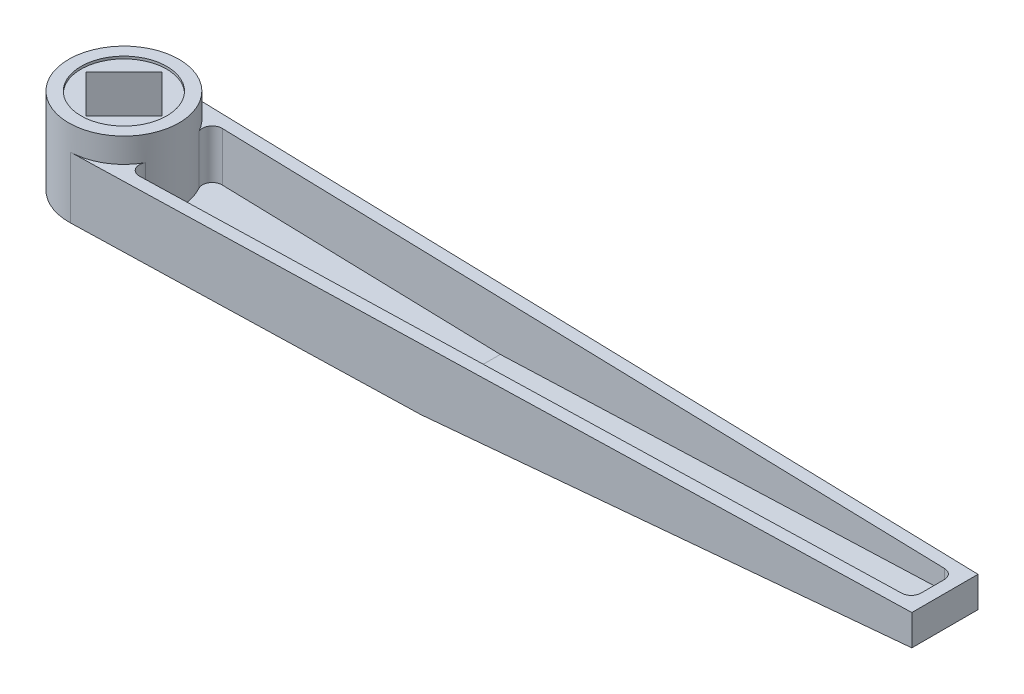
SolidWorks part; units mm, degrees
material "1060 Alloy"
ref_plane "XY" through (0, 0, 0) normal (0, 0, 1) x (1, 0, 0)
ref_plane "XZ" through (0, 0, 0) normal (0, 1, 0) x (1, 0, 0)
ref_plane "YZ" through (0, 0, 0) normal (1, 0, 0) x (0, 0, -1)
sketch "A" plane through (0, 0, 0) normal (0, 1, 0) x (1, 0, 0)
  line L0 (0, 0) -> (335, 0) construction
  line L1 (0.6048, 22.4919) -> (335, 13.5)
  line L2 (335, 13.5) -> (335, -13.5)
  line L3 (0.6048, -22.4919) -> (335, -13.5)
  line L4 (0.6048, 22.4919) -> (0.6048, -22.4919)
  circle A0 centre (0, 0) radius 22.5
  dimension "D1" = 45
  dimension "D2" = 27
  dimension "D3" = 335
extrude "X1" add sketch "A" along normal blind 25 contours L0 A0 L3 L2 | A0 L0 L2 L1
sketch "B" plane through (0, 0, 0) normal (0, 0, 1) x (1, 0, 0)
  line L0 (335, 12.5) -> (140, 0)
  line L1 (335, 25) -> (335, 0) construction
  line L2 (0.6048, 0) -> (335, 0) construction
  line L3 (140, 0) -> (140, -74.1467)
  line L4 (140, -74.1467) -> (362.4662, -74.1467)
  line L5 (362.4662, -74.1467) -> (356.9119, 12.5)
  line L6 (356.9119, 12.5) -> (335, 12.5)
  dimension "D1" = 195
extrude "X2" cut sketch "B" against normal through all and the other way through all
shell "S1" thickness 5
sketch "C" plane through (0, 0, 0) normal (0, 1, 0) x (1, 0, 0)
  circle A0 centre (0, 0) radius 22.5 construction
  circle A1 centre (0, 0) radius 22.5
extrude "X3" add sketch "C" along normal blind 35
sketch "D" plane through (0, 35, 0) normal (0, 1, 0) x (1, 0, 0)
  circle A0 centre (0, 0) radius 17.5
  dimension "D1" = 35
extrude "X5" cut sketch "D" against normal blind 1
sketch "E" plane through (0, 0, 0) normal (0, -1, 0) x (1, 0, 0)
  circle A1 centre (0, 0) radius 17.5
  dimension "D1" = 35
extrude "X6" cut sketch "E" against normal blind 1
sketch "F" plane through (0, 1, 0) normal (0, 1, 0) x (1, 0, 0)
  line L1 (0, 15.5563) -> (-15.5563, 0)
  line L2 (0, 15.5563) -> (15.5563, 0)
  line L3 (15.5563, 0) -> (0, -15.5563)
  line L4 (-15.5563, 0) -> (0, -15.5563)
  line L5 (0, 15.5563) -> (0, -15.5563) construction
  line L6 (15.5563, 0) -> (-15.5563, 0) construction
  point P0 (0, 0)
  dimension "D1" = 22
  dimension "D2" = 22
extrude "X7" cut sketch "F" along normal through all
fillet "F1" radius 4 4 edges at (330, 21.0949, 8.6326) (330, 21.0949, -8.6326) (14.6074, 15, -17.1135) (14.6074, 15, 17.1135)
